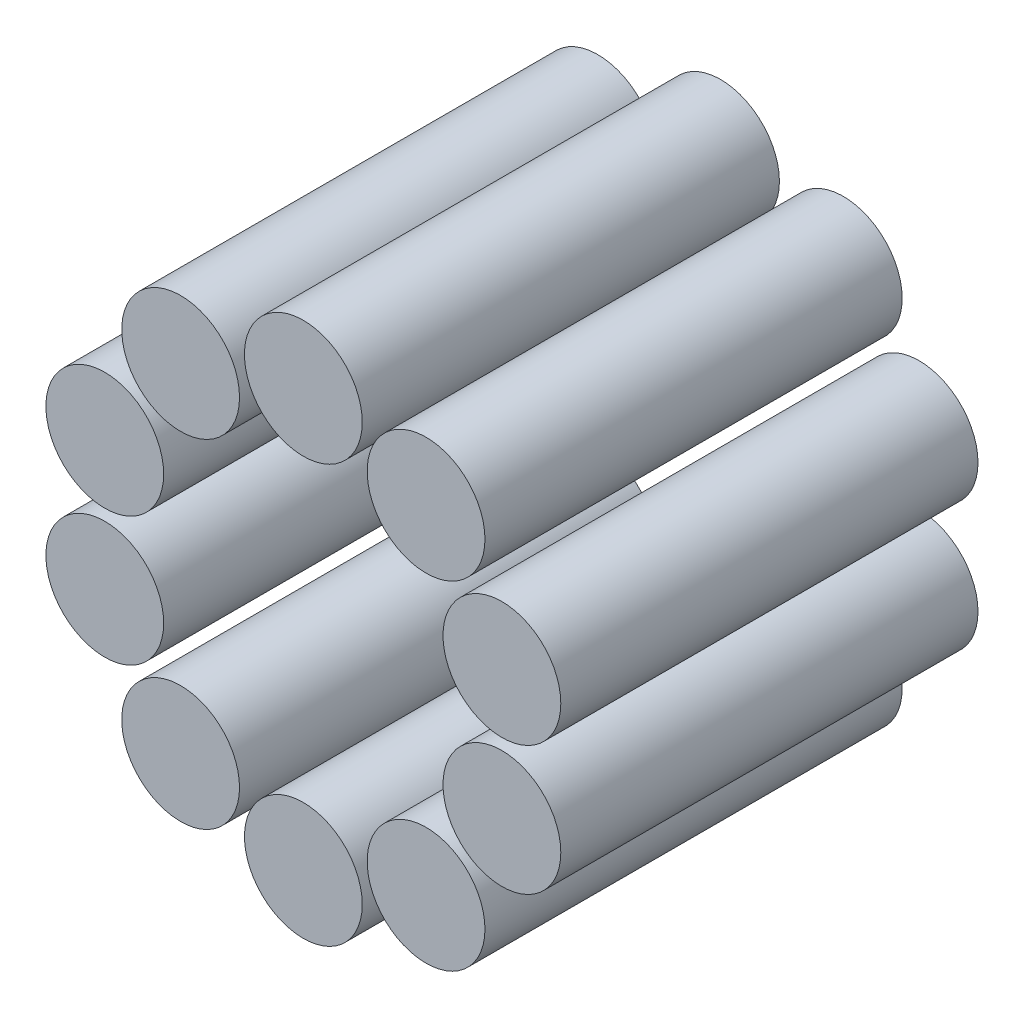
SolidWorks part; units mm, degrees
ref_plane "Front Plane" through (0, 0, 0) normal (0, 0, 1) x (1, 0, 0)
ref_plane "Top Plane" through (0, 0, 0) normal (0, 1, 0) x (1, 0, 0)
ref_plane "Right Plane" through (0, 0, 0) normal (1, 0, 0) x (0, 0, -1)
sketch "Sketch2" plane through (0, 0, 0) normal (0, 0, 1) x (1, 0, 0)
  circle A0 centre (0, 0) radius 32.53 construction
  circle A1 centre (0, -32.53) radius 9.175
  circle A2 centre (-19.1207, -26.3173) radius 9.175
  circle A3 centre (-30.9379, -10.0523) radius 9.175
  circle A4 centre (-30.9379, 10.0523) radius 9.175
  circle A5 centre (-19.1207, 26.3173) radius 9.175
  circle A6 centre (0, 32.53) radius 9.175
  circle A7 centre (19.1207, 26.3173) radius 9.175
  circle A8 centre (30.9379, 10.0523) radius 9.175
  circle A9 centre (30.9379, -10.0523) radius 9.175
  circle A10 centre (19.1207, -26.3173) radius 9.175
  point P25 (0, 0)
  dimension "D1" = 65.06
  dimension "D2" = 18.35
  dimension "D3" = 10
extrude "Boss-Extrude1" add sketch "Sketch2" along normal blind 65
